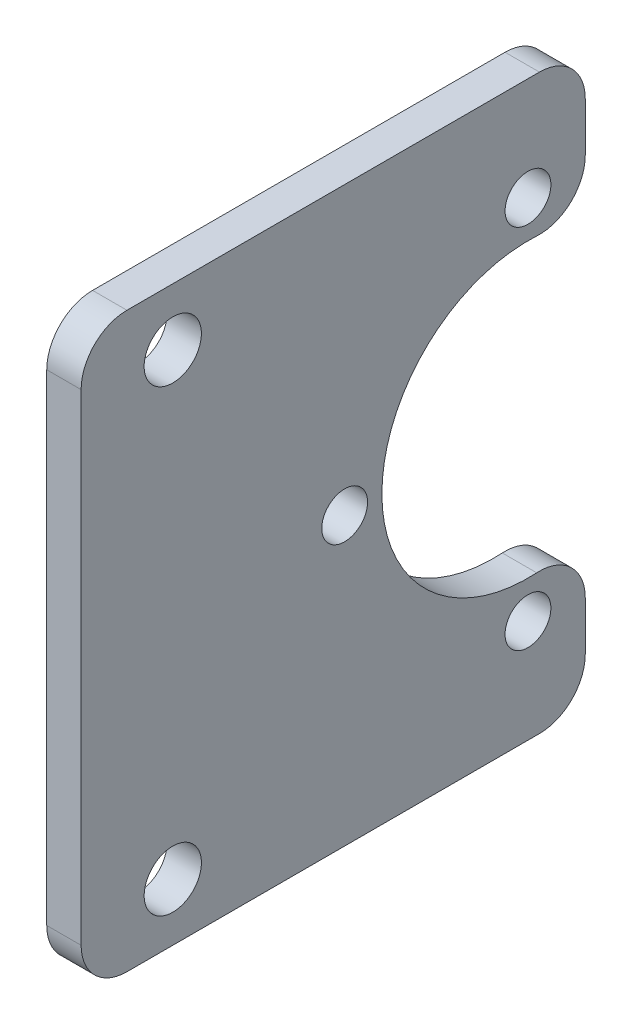
SolidWorks part; units mm, degrees
material "3.0205 (EN-AW 1200)"
ref_plane "Plan de face" through (0, 0, 0) normal (0, 0, 1) x (1, 0, 0)
ref_plane "Plan de dessus" through (0, 0, 0) normal (0, 1, 0) x (1, 0, 0)
ref_plane "Plan de droite" through (0, 0, 0) normal (1, 0, 0) x (0, 0, -1)
sketch "Esquisse1" plane through (0, 0, 0) normal (1, 0, 0) x (0, 0, -1)
  line L0 (0, 0) -> (23, 0) construction
  line L1 (0, 25) -> (44, 25)
  line L2 (0, 25) -> (0, -25)
  line L3 (44, 25) -> (44, 11.7287)
  line L4 (0, -25) -> (44, -25)
  line L5 (23, 0) -> (39, 0) construction
  line L6 (39, 0) -> (39, 16) construction
  line L7 (44, -11.7287) -> (44, -25)
  arc A0 (44, 11.7287) -> (44, -11.7287) centre (39, 0) ccw
  circle A1 centre (39, 16) radius 2
  circle A2 centre (23, 0) radius 2
  circle A3 centre (39, -16) radius 2
  circle A4 centre (8, 20) radius 2.5
  circle A5 centre (8, -20) radius 2.5
  dimension "D1" = 4
  dimension "D3" = 25.5
  dimension "D4" = 8
  dimension "D5" = 31
  dimension "D6" = 5
  dimension "D7" = 40
  dimension "D9" = 5
  dimension "D10" = 5
  dimension "D2" = 16
extrude "Boss.-Extru.1" add sketch "Esquisse1" along normal blind 3
fillet "Congé1" radius 4 6 edges at (1.5, 25, -44) (1.5, 11.7287, -44) (1.5, -11.7287, -44) (1.5, -25, -44) (1.5, -25, 0) (1.5, 25, 0)
